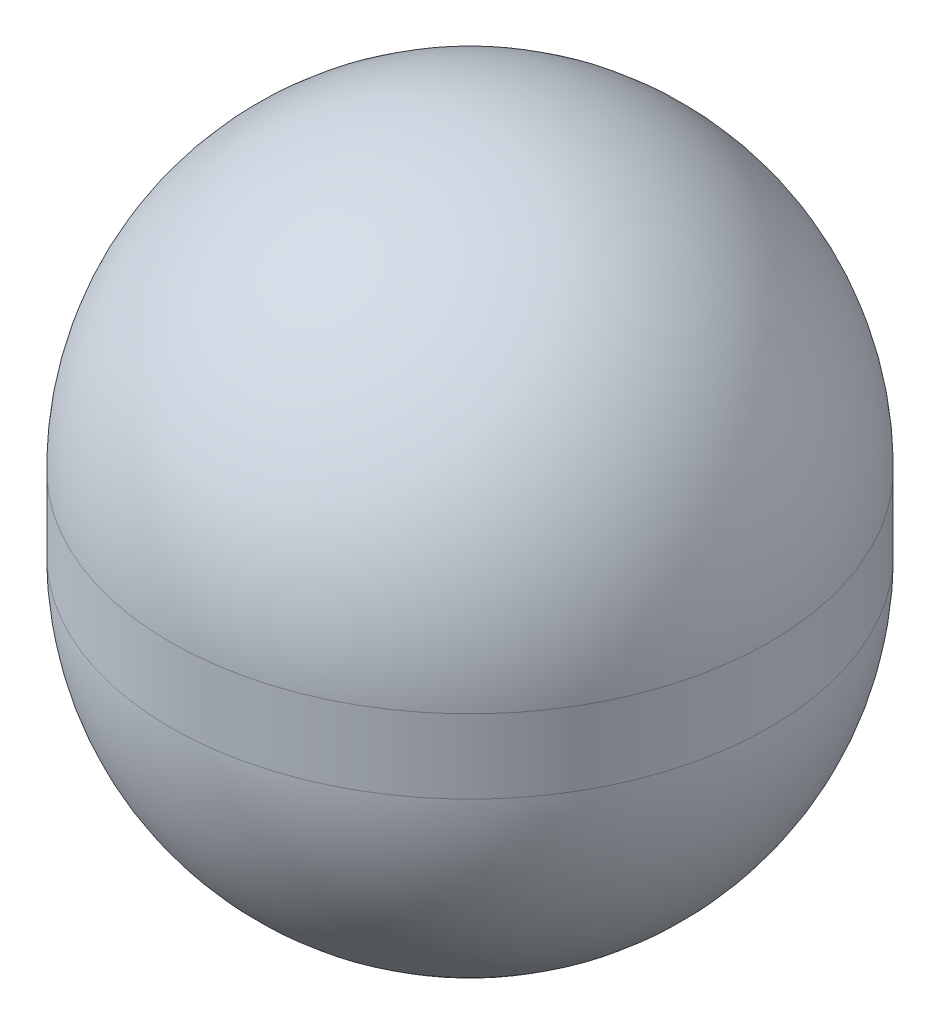
SolidWorks part; units mm, degrees
ref_plane "Front Plane" through (0, 0, 0) normal (0, 0, 1) x (1, 0, 0)
ref_plane "Top Plane" through (0, 0, 0) normal (0, 1, 0) x (1, 0, 0)
ref_plane "Right Plane" through (0, 0, 0) normal (1, 0, 0) x (0, 0, -1)
sketch "Sketch1" plane through (0, 0, 0) normal (0, 1, 0) x (1, 0, 0)
  line L0 (0, -30.898) -> (0, 30.898)
  line L1 (0, -30.898) -> (0, 30.898) construction
  arc A0 (0, -30.898) -> (0, 30.898) centre (0, 0) ccw
revolve "Revolve1" add sketch "Sketch1" angle 180 about L1
sketch "Sketch2" plane through (0, 0, 0) normal (0, 1, 0) x (1, 0, 0)
  circle A0 centre (0, 0) radius 30.898
extrude "Boss-Extrude1" add sketch "Sketch2" along normal blind 7.62
sketch "Sketch3" plane through (0, 7.62, 0) normal (0, 1, 0) x (1, 0, 0)
  line L0 (0, 30.898) -> (0, -30.898)
  line L1 (0, 30.898) -> (0, -30.898) construction
  arc A0 (0, 30.898) -> (0, -30.898) centre (0, 0) cw
  circle A1 centre (0, 0) radius 30.898 construction
revolve "Revolve2" add sketch "Sketch3" angle 180 about L1
